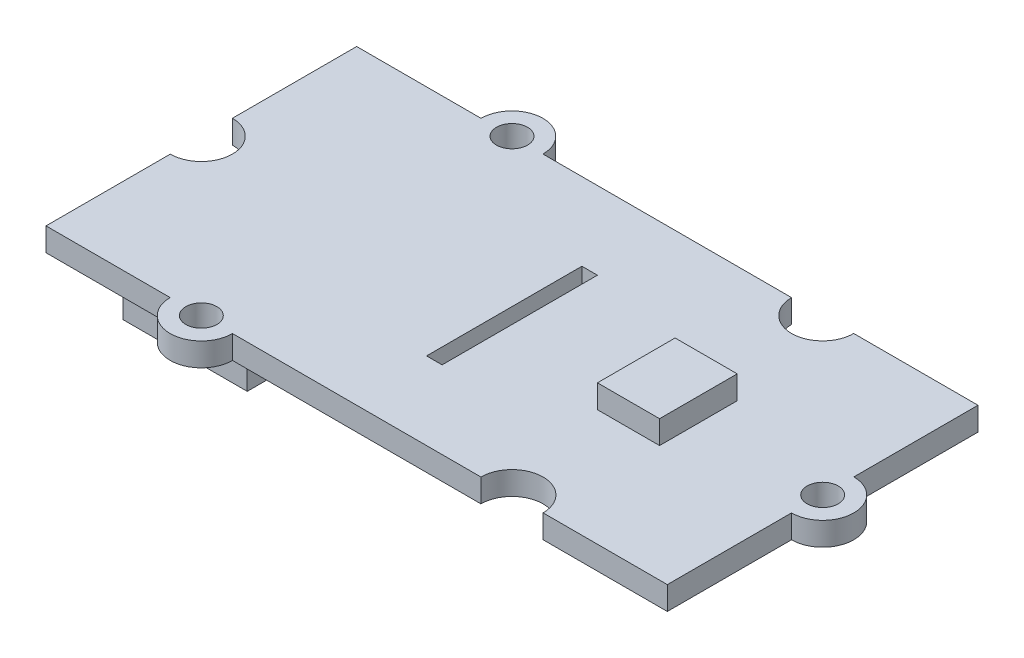
SolidWorks part; units mm, degrees
ref_plane "Plan de face" through (0, 0, 0) normal (0, 0, 1) x (1, 0, 0)
ref_plane "Plan de dessus" through (0, 0, 0) normal (0, 1, 0) x (1, 0, 0)
ref_plane "Plan de droite" through (0, 0, 0) normal (1, 0, 0) x (0, 0, -1)
sketch "Esquisse1" plane through (0, 0, 0) normal (0, 1, 0) x (1, 0, 0)
  line L0 (0, 10) -> (0, -10) construction
  line L1 (-20, -10) -> (20, -10)
  line L2 (-20, -10) -> (-20, 10)
  line L3 (-20, 10) -> (20, 10)
  line L4 (20, -10) -> (20, 10)
  line L5 (-20, -10) -> (20, 10) construction
  line L6 (-20, 10) -> (20, -10) construction
  line L8 (-0.5, -5) -> (0.5, -5)
  line L9 (-0.5, -5) -> (-0.5, 5)
  line L10 (-0.5, 5) -> (0.5, 5)
  line L11 (0.5, -5) -> (0.5, 5)
  line L12 (-0.5, -5) -> (0.5, 5) construction
  line L13 (-0.5, 5) -> (0.5, -5) construction
  circle A0 centre (-10, 10) radius 1
  circle A1 centre (-10, -10) radius 1
  circle A2 centre (20, 0) radius 1
  arc A3 (-8.0064, 10) -> (-11.9936, 10) centre (-10, 10) ccw
  arc A4 (-12.0064, -10) -> (-7.9936, -10) centre (-10, -10) ccw
  arc A5 (20, -2.0064) -> (20, 2.0064) centre (20, 0) ccw
  circle A6 centre (10, -10) radius 2
  circle A7 centre (10, 10) radius 2
  circle A8 centre (-20, 0) radius 2
  point P0 (0, 0)
  point P26 (0, 0)
  point P31 (-10, 11.9936)
  point P32 (-10, -12.0064)
  dimension "D3" = 2
  dimension "D5" = 4
  dimension "D1" = 40
  dimension "D2" = 20
  dimension "D4" = 10
  dimension "D6" = 1
  dimension "D7" = 10
  dimension "D8" = 24
  dimension "D9" = 10
extrude "Base" add sketch "Esquisse1" along normal blind 1.5 contours A8 L2 L1 A1 A6 L4 A2 L3 A7 A0 L11 L8 L9 L10 | L3 A3 A0 | L4 A5 A2 | L1 A4 A1
sketch "Esquisse2" plane through (0, 1.5, 0) normal (0, 1, 0) x (1, 0, 0)
  line L0 (0, 0) -> (0, 10) construction
  line L1 (-8.0064, 10) -> (8, 10) construction
  line L2 (0, 0) -> (0, -10) construction
  line L3 (-7.9936, -10) -> (8, -10) construction
  line L4 (0, -10) -> (20, 10) construction
  line L6 (8, -2.5) -> (12, -2.5)
  line L7 (8, -2.5) -> (8, 2.5)
  line L8 (8, 2.5) -> (12, 2.5)
  line L9 (12, -2.5) -> (12, 2.5)
  line L10 (8, -2.5) -> (12, 2.5) construction
  line L11 (8, 2.5) -> (12, -2.5) construction
  point P9 (10, 0)
  dimension "D1" = 4
  dimension "D2" = 5
extrude "SOIC-8" add sketch "Esquisse2" along normal blind 1.5
sketch "Esquisse3" plane through (0, 0, 0) normal (0, 1, 0) x (1, 0, 0)
  line L0 (-18, 0) -> (-0.5, 0) construction
  line L1 (-19.0442, -6) -> (-11.0442, -6)
  line L2 (-19.0442, -6) -> (-19.0442, 6)
  line L3 (-19.0442, 6) -> (-11.0442, 6)
  line L4 (-11.0442, -6) -> (-11.0442, 6)
  line L5 (-19.0442, -6) -> (-11.0442, 6) construction
  line L6 (-19.0442, 6) -> (-11.0442, -6) construction
  line L7 (-0.5, -5) -> (-0.5, 5) construction
  arc A0 (-20, -2) -> (-20, 2) centre (-20, 0) ccw construction
  point P0 (-15.0442, 0)
  dimension "D1" = 12
  dimension "D2" = 8
extrude "Grove connector" add sketch "Esquisse3" against normal blind 5.25
